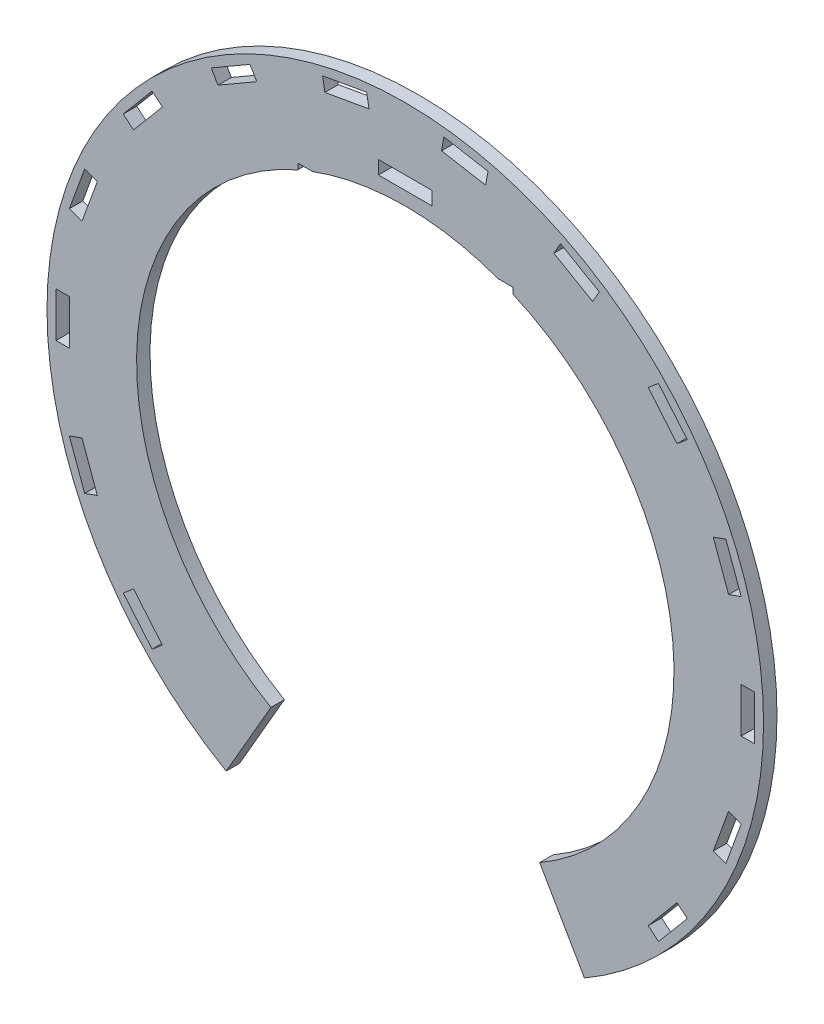
SolidWorks part; units mm, degrees
ref_plane "Přední rovina" through (0, 0, 0) normal (0, 0, 1) x (1, 0, 0)
ref_plane "Horní rovina" through (0, 0, 0) normal (0, 1, 0) x (1, 0, 0)
ref_plane "Pravá rovina" through (0, 0, 0) normal (1, 0, 0) x (0, 0, -1)
sketch "Skica1" plane through (0, 0, 0) normal (0, 0, 1) x (1, 0, 0)
  line L0 (-82.0154, 0) -> (100.8716, 0) construction
  line L1 (0, 71.1227) -> (0, -71.1227) construction
  line L2 (-40, -69.282) -> (-30, -51.9615)
  line L3 (50.2914, 87.1072) -> (-43.916, -76.0647) construction
  line L4 (40, -69.282) -> (-42.9451, 74.3831) construction
  line L5 (40, -69.282) -> (30, -51.9615)
  arc A0 (40, -69.282) -> (-40, -69.282) centre (0, 0) ccw
  arc A1 (30, -51.9615) -> (-30, -51.9615) centre (0, 0) ccw
  dimension "D4" = 80
  dimension "D1" = 30
  dimension "D2" = 30
  dimension "D3" = 20
extrude "Přidat vysunutím1" add sketch "Skica1" along normal blind 3
sketch "Skica3" plane through (0, 0, 3) normal (0, 0, 1) x (1, 0, 0)
  line L0 (-43.3301, 65.05) -> (-34.6699, 70.05)
  line L1 (-67.9025, -69.282) -> (98.6253, -69.282) construction
  line L2 (-40, -69.282) -> (0, 0) construction
  line L3 (0, 0) -> (55.5524, 96.2196) construction
  line L4 (40, -69.282) -> (0, 0) construction
  line L5 (-6, 63) -> (6, 63)
  line L6 (0, 0) -> (96.2196, 55.5524) construction
  line L7 (0, 0) -> (111.1049, 0) construction
  line L8 (0, 0) -> (96.2196, -55.5524) construction
  line L9 (0, 0) -> (55.5524, -96.2196) construction
  line L10 (-6, 63) -> (-6, 66)
  line L11 (0, 0) -> (-55.5524, -96.2196) construction
  line L12 (0, 0) -> (-96.2196, -55.5524) construction
  line L13 (0, 0) -> (-111.1049, 0) construction
  line L14 (0, 0) -> (-96.2196, 55.5524) construction
  line L15 (0, 0) -> (-55.5524, 96.2196) construction
  line L16 (0, 0) -> (0, 111.1049) construction
  line L17 (0, 0) -> (0, -111.1049) construction
  line L18 (-6, 66) -> (6, 66)
  line L19 (6, 63) -> (6, 66)
  line L20 (-6, 63) -> (6, 66) construction
  line L21 (-6, 66) -> (6, 63) construction
  line L22 (-43.3301, 65.05) -> (-41.8301, 62.4519)
  line L23 (-34.6699, 70.05) -> (-33.1699, 67.4519)
  line L24 (-41.8301, 62.4519) -> (-33.1699, 67.4519)
  line L25 (-43.3301, 65.05) -> (-33.1699, 67.4519) construction
  line L26 (-34.6699, 70.05) -> (-41.8301, 62.4519) construction
  line L27 (-18.4686, 75.9468) -> (-8.6205, 77.6832)
  line L28 (-18.4686, 75.9468) -> (-17.9477, 72.9923)
  line L29 (-17.9477, 72.9923) -> (-8.0996, 74.7288)
  line L30 (-8.6205, 77.6832) -> (-8.0996, 74.7288)
  line L31 (8.6205, 77.6832) -> (18.4686, 75.9468)
  line L32 (8.6205, 77.6832) -> (8.0996, 74.7288)
  line L33 (8.0996, 74.7288) -> (17.9477, 72.9923)
  line L34 (18.4686, 75.9468) -> (17.9477, 72.9923)
  line L35 (34.6699, 70.05) -> (43.3301, 65.05)
  line L36 (34.6699, 70.05) -> (33.1699, 67.4519)
  line L37 (33.1699, 67.4519) -> (41.8301, 62.4519)
  line L38 (43.3301, 65.05) -> (41.8301, 62.4519)
  line L39 (56.5375, 53.9677) -> (62.9654, 46.3072)
  line L40 (56.5375, 53.9677) -> (54.2394, 52.0393)
  line L41 (54.2394, 52.0393) -> (60.6673, 44.3788)
  line L42 (62.9654, 46.3072) -> (60.6673, 44.3788)
  line L43 (71.5859, 31.376) -> (75.0061, 21.9791)
  line L44 (71.5859, 31.376) -> (68.7668, 30.35)
  line L45 (68.7668, 30.35) -> (72.187, 20.953)
  line L46 (75.0061, 21.9791) -> (72.187, 20.953)
  line L47 (78, 5) -> (78, -5)
  line L48 (78, 5) -> (75, 5)
  line L49 (75, 5) -> (75, -5)
  line L50 (78, -5) -> (75, -5)
  line L51 (75.0061, -21.9791) -> (71.5859, -31.376)
  line L52 (75.0061, -21.9791) -> (72.187, -20.953)
  line L53 (72.187, -20.953) -> (68.7668, -30.35)
  line L54 (71.5859, -31.376) -> (68.7668, -30.35)
  line L55 (62.9654, -46.3072) -> (56.5375, -53.9677)
  line L56 (62.9654, -46.3072) -> (60.6673, -44.3788)
  line L57 (60.6673, -44.3788) -> (54.2394, -52.0393)
  line L58 (56.5375, -53.9677) -> (54.2394, -52.0393)
  line L59 (43.3301, -65.05) -> (34.6699, -70.05) [skipped]
  line L60 (43.3301, -65.05) -> (41.8301, -62.4519) [skipped]
  line L61 (41.8301, -62.4519) -> (33.1699, -67.4519) [skipped]
  line L62 (34.6699, -70.05) -> (33.1699, -67.4519) [skipped]
  line L63 (18.4686, -75.9468) -> (8.6205, -77.6832) [skipped]
  line L64 (18.4686, -75.9468) -> (17.9477, -72.9923) [skipped]
  line L65 (17.9477, -72.9923) -> (8.0996, -74.7288) [skipped]
  line L66 (8.6205, -77.6832) -> (8.0996, -74.7288) [skipped]
  line L67 (-8.6205, -77.6832) -> (-18.4686, -75.9468) [skipped]
  line L68 (-8.6205, -77.6832) -> (-8.0996, -74.7288) [skipped]
  line L69 (-8.0996, -74.7288) -> (-17.9477, -72.9923) [skipped]
  line L70 (-18.4686, -75.9468) -> (-17.9477, -72.9923) [skipped]
  line L71 (-34.6699, -70.05) -> (-43.3301, -65.05) [skipped]
  line L72 (-34.6699, -70.05) -> (-33.1699, -67.4519) [skipped]
  line L73 (-33.1699, -67.4519) -> (-41.8301, -62.4519) [skipped]
  line L74 (-43.3301, -65.05) -> (-41.8301, -62.4519) [skipped]
  line L75 (-56.5375, -53.9677) -> (-62.9654, -46.3072)
  line L76 (-56.5375, -53.9677) -> (-54.2394, -52.0393)
  line L77 (-54.2394, -52.0393) -> (-60.6673, -44.3788)
  line L78 (-62.9654, -46.3072) -> (-60.6673, -44.3788)
  line L79 (-71.5859, -31.376) -> (-75.0061, -21.9791)
  line L80 (-71.5859, -31.376) -> (-68.7668, -30.35)
  line L81 (-68.7668, -30.35) -> (-72.187, -20.953)
  line L82 (-75.0061, -21.9791) -> (-72.187, -20.953)
  line L83 (-78, -5) -> (-78, 5)
  line L84 (-78, -5) -> (-75, -5)
  line L85 (-75, -5) -> (-75, 5)
  line L86 (-78, 5) -> (-75, 5)
  line L87 (-75.0061, 21.9791) -> (-71.5859, 31.376)
  line L88 (-75.0061, 21.9791) -> (-72.187, 20.953)
  line L89 (-72.187, 20.953) -> (-68.7668, 30.35)
  line L90 (-71.5859, 31.376) -> (-68.7668, 30.35)
  line L91 (-62.9654, 46.3072) -> (-56.5375, 53.9677)
  line L92 (-62.9654, 46.3072) -> (-60.6673, 44.3788)
  line L93 (-60.6673, 44.3788) -> (-54.2394, 52.0393)
  line L94 (-56.5375, 53.9677) -> (-54.2394, 52.0393)
  arc A0 (30, -51.9615) -> (-30, -51.9615) centre (0, 0) ccw construction
  point P0 (0, 64.5)
  point P3 (0, 0)
  point P4 (-40, -69.282)
  point P5 (40, -69.282)
  point P30 (0, 0)
  point P33 (0, 60)
  point P35 (-38.25, 66.2509)
  point P37 (-30, 51.9615)
  point P39 (-38.3657, 66.4513)
  point P112 (0, 0)
  dimension "D2" = 3
  dimension "D3" = 12
  dimension "D4" = 3
  dimension "D5" = 5
  dimension "D6" = 10
  dimension "D7" = 3
  dimension "D9" = 78
  dimension "D1" = 12
  dimension "D8" = 18
extrude "Odebrat vysunutím1" cut sketch "Skica3" against normal blind 3
sketch "Skica4" plane through (0, 0, 0) normal (0, 0, -1) x (-1, 0, 0)
  line L0 (0, 85.4839) -> (0, 30.8548) construction
  line L2 (-24, 56.31) -> (24, 56.31)
  line L3 (-24, 56.31) -> (-24, 52.81)
  line L4 (-24, 52.81) -> (24, 52.81)
  line L5 (24, 56.31) -> (24, 52.81)
  line L6 (-24, 56.31) -> (24, 52.81) construction
  line L7 (-24, 52.81) -> (24, 56.31) construction
  point P2 (0, 54.56)
  point P8 (0, 0)
  point P9 (20.5414, 54.7138)
  dimension "D1" = 52.81
  dimension "D2" = 48
  dimension "D3" = 3.5
extrude "Odebrat vysunutím3" cut sketch "Skica4" against normal blind 3 contours L3 L2 L5 L4
